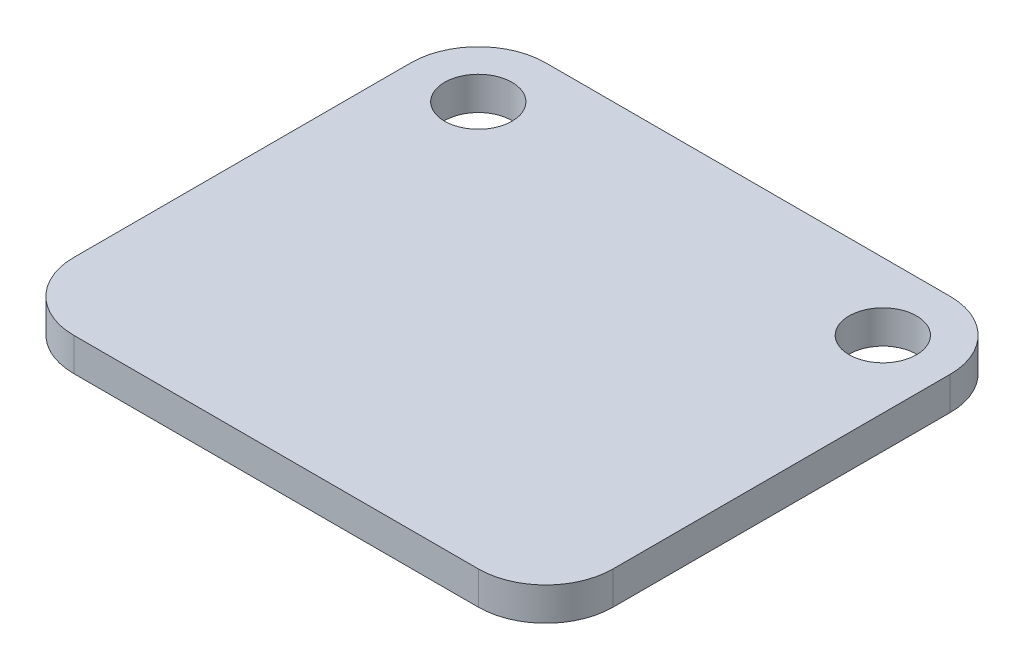
SolidWorks part; units mm, degrees
ref_plane "Front Plane" through (0, 0, 0) normal (0, 0, 1) x (1, 0, 0)
ref_plane "Top Plane" through (0, 0, 0) normal (0, 1, 0) x (1, 0, 0)
ref_plane "Right Plane" through (0, 0, 0) normal (1, 0, 0) x (0, 0, -1)
sketch "Sketch1" plane through (0, 0, 0) normal (0, 1, 0) x (1, 0, 0)
  line L0 (-10.16, 0) -> (10.16, 0) construction
  line L1 (-7.62, -8.89) -> (7.62, -8.89)
  line L2 (-10.16, -6.35) -> (-10.16, 6.35)
  line L3 (-10.16, 8.89) -> (-7.62, 8.89) construction
  line L4 (10.16, -6.35) -> (10.16, 6.35)
  line L5 (0, 8.89) -> (0, -8.89) construction
  line L6 (-7.62, 6.35) -> (7.62, 6.35) construction
  line L7 (7.62, 6.35) -> (7.62, 8.89) construction
  line L8 (7.62, 6.35) -> (10.16, 6.35) construction
  line L9 (7.62, 8.89) -> (10.16, 8.89) construction
  line L10 (10.16, 6.35) -> (10.16, 8.89) construction
  line L11 (-10.16, 6.35) -> (-10.16, 8.89) construction
  line L12 (-7.62, 8.89) -> (7.62, 8.89)
  circle A0 centre (-7.62, 6.35) radius 1.27
  circle A1 centre (7.62, 6.35) radius 1.27
  arc A2 (7.62, 8.89) -> (10.16, 6.35) centre (7.62, 6.35) cw
  arc A3 (-7.62, 8.89) -> (-10.16, 6.35) centre (-7.62, 6.35) ccw
  arc A4 (10.16, -6.35) -> (7.62, -8.89) centre (7.62, -6.35) cw
  arc A5 (-7.62, -8.89) -> (-10.16, -6.35) centre (-7.62, -6.35) cw
  point P0 (0, 0)
  point P14 (0, 6.35)
  point P19 (-8.9428, 8.6756)
  point P22 (0, 0)
  point P23 (0, 0)
  point P24 (0, 0)
  point P29 (-10.16, -8.89)
  dimension "D4" = 2.54
  dimension "D1" = 20.32
  dimension "D2" = 17.78
  dimension "D3" = 15.24
extrude "Boss-Extrude1" add sketch "Sketch1" along normal blind 1.25 contours A5 L1 A4 L4 A2 L12 A3 L2 A1 A0
